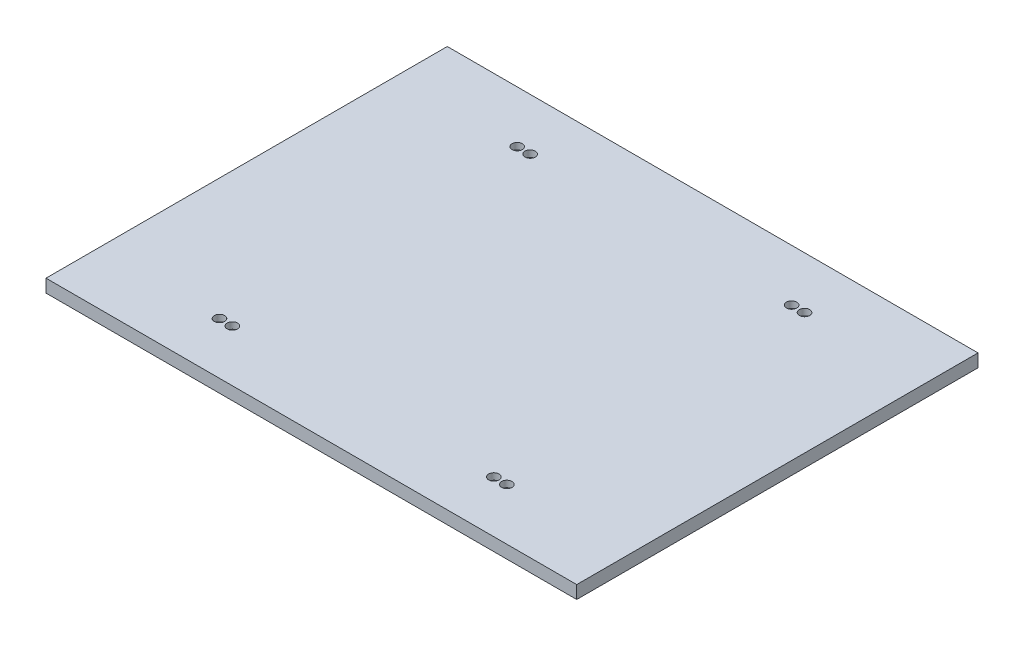
SolidWorks part; units mm, degrees
material "Acrylic (Medium-high impact)"
ref_plane "Front Plane" through (0, 0, 0) normal (0, 0, 1) x (1, 0, 0)
ref_plane "Top Plane" through (0, 0, 0) normal (0, 1, 0) x (1, 0, 0)
ref_plane "Right Plane" through (0, 0, 0) normal (1, 0, 0) x (0, 0, -1)
sketch "Sketch1" plane through (0, 0, 0) normal (0, 1, 0) x (1, 0, 0)
  line L1 (0, 0) -> (410, 0)
  line L2 (0, 0) -> (0, 310)
  line L3 (0, 310) -> (410, 310)
  line L4 (410, 0) -> (410, 310)
  dimension "D1" = 310
  dimension "D2" = 410
extrude "Boss-Extrude1" add sketch "Sketch1" along normal blind 10
sketch "Sketch2" plane through (0, 10, 0) normal (0, 1, 0) x (1, 0, 0)
  line L0 (0, 310) -> (0, 0) construction
  line L1 (410, 0) -> (410, 310) construction
  line L2 (0, 0) -> (410, 0) construction
  circle A0 centre (94, 40) radius 2
  circle A1 centre (104, 40) radius 2
  circle A2 centre (306, 40) radius 2
  circle A3 centre (316, 40) radius 2
  circle A4 centre (316, 270) radius 2
  circle A5 centre (306, 270) radius 2
  circle A6 centre (104, 270) radius 2
  circle A7 centre (94, 270) radius 2
  dimension "D1" = 94
  dimension "D5" = 4
  dimension "D2" = 94
  dimension "D3" = 10
  dimension "D4" = 10
  dimension "D6" = 40
  dimension "D7" = 230
extrude "Cut-Extrude1" cut sketch "Sketch2" against normal through all
sketch "Sketch3" plane through (0, 10, 0) normal (0, 1, 0) x (1, 0, 0)
  circle A0 centre (94, 270) radius 4
  circle A1 centre (104, 270) radius 4
  circle A2 centre (306, 270) radius 4
  circle A3 centre (316, 270) radius 4
  circle A4 centre (306, 40) radius 4
  circle A5 centre (316, 40) radius 4
  circle A6 centre (94, 40) radius 4
  circle A7 centre (104, 40) radius 4
  dimension "D1" = 8
extrude "Cut-Extrude2" cut sketch "Sketch3" against normal blind 5
